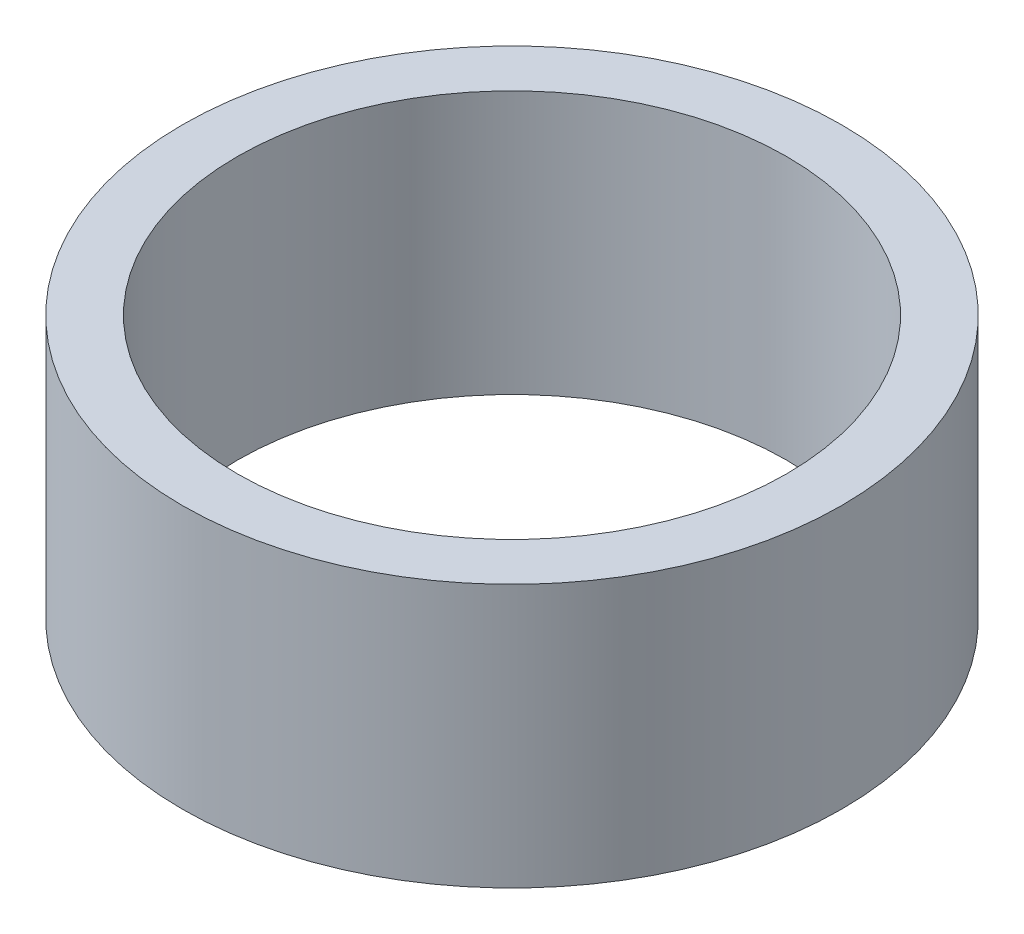
SolidWorks part; units mm, degrees
material "Alumina"
ref_plane "Front Plane" through (0, 0, 0) normal (0, 0, 1) x (1, 0, 0)
ref_plane "Top Plane" through (0, 0, 0) normal (0, 1, 0) x (1, 0, 0)
ref_plane "Right Plane" through (0, 0, 0) normal (1, 0, 0) x (0, 0, -1)
sketch "Sketch2" plane through (0, 0, 0) normal (0, 1, 0) x (1, 0, 0)
  circle A0 centre (0, 0) radius 60
  circle A1 centre (0, 0) radius 50
  dimension "D1" = 100
  dimension "D2" = 120
extrude "Boss-Extrude1" add sketch "Sketch2" along normal blind 47.86
